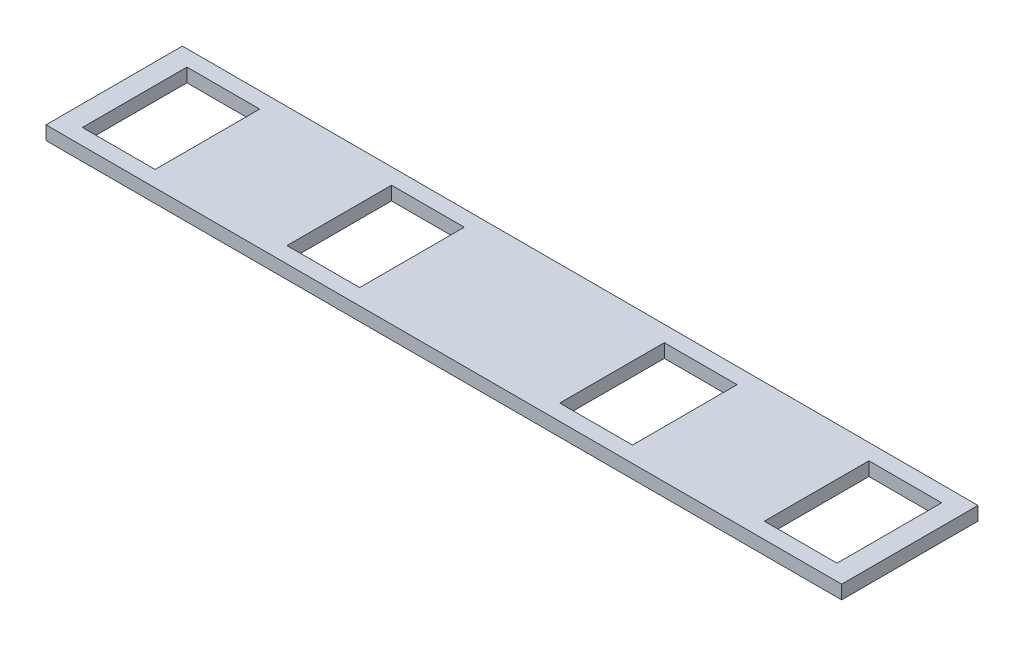
SolidWorks part; units mm, degrees
ref_plane "Front Plane" through (0, 0, 0) normal (0, 0, 1) x (1, 0, 0)
ref_plane "Top Plane" through (0, 0, 0) normal (0, 1, 0) x (1, 0, 0)
ref_plane "Right Plane" through (0, 0, 0) normal (1, 0, 0) x (0, 0, -1)
sketch "Croquis1" plane through (0, 0, 0) normal (0, 1, 0) x (1, 0, 0)
  line L0 (-83, -11.5) -> (-83, 11.5)
  line L1 (-87.5, -15) -> (87.5, -15)
  line L2 (-87.5, -15) -> (-87.5, 15)
  line L3 (-87.5, 15) -> (87.5, 15)
  line L4 (87.5, -15) -> (87.5, 15)
  line L5 (-87.5, -15) -> (87.5, 15) construction
  line L6 (-87.5, 15) -> (87.5, -15) construction
  line L11 (22, -11.5) -> (22, 11.5)
  line L12 (-38, -11.5) -> (-22, -11.5)
  line L13 (0, 0) -> (0, 50000) construction
  line L18 (-38, -11.5) -> (-38, 11.5)
  line L19 (-38, 11.5) -> (-22, 11.5)
  line L20 (-22, -11.5) -> (-22, 11.5)
  line L21 (-38, -11.5) -> (-22, 11.5) construction
  line L22 (-38, 11.5) -> (-22, -11.5) construction
  line L23 (38, -11.5) -> (22, -11.5)
  line L24 (38, -11.5) -> (38, 11.5)
  line L25 (38, 11.5) -> (22, 11.5)
  line L26 (-83, 11.5) -> (-67, 11.5)
  line L27 (-67, -11.5) -> (-67, 11.5)
  line L28 (-83, -11.5) -> (-67, -11.5)
  line L29 (83, 11.5) -> (67, 11.5)
  line L30 (67, -11.5) -> (67, 11.5)
  line L31 (83, -11.5) -> (67, -11.5)
  line L32 (83, -11.5) -> (83, 11.5)
  point P0 (0, 0)
  point P5 (-30, 0)
  dimension "D1" = 175
  dimension "D2" = 16
  dimension "D3" = 23
  dimension "D4" = 30
  dimension "D5" = 2
  dimension "D6" = 2
extrude "Saliente-Extruir1" add sketch "Croquis1" along normal blind 3
